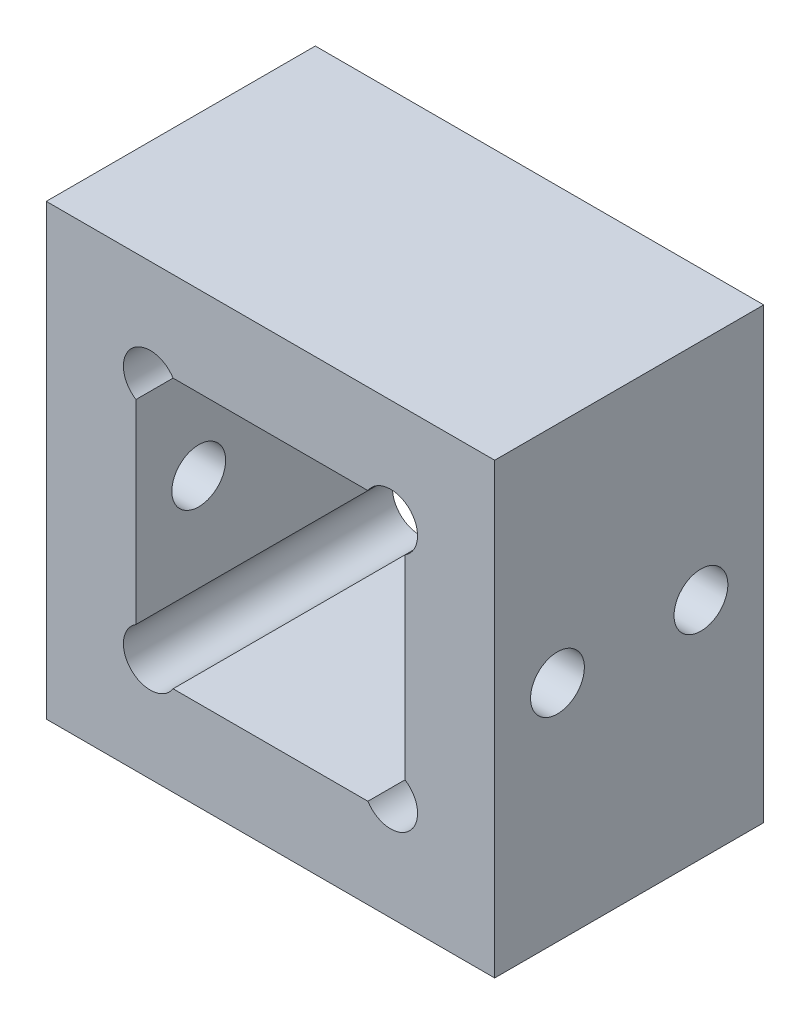
SolidWorks part; units mm, degrees
material "POM 乙缩醛共聚物"
ref_plane "前视基准面" through (0, 0, 0) normal (0, 0, 1) x (1, 0, 0)
ref_plane "上视基准面" through (0, 0, 0) normal (0, 1, 0) x (1, 0, 0)
ref_plane "右视基准面" through (0, 0, 0) normal (1, 0, 0) x (0, 0, -1)
sketch "草图1" plane through (0, 0, 0) normal (0, 0, 1) x (1, 0, 0)
  line L0 (-12.5, 12.5) -> (12.5, 12.5)
  line L5 (-7.5, 7.5) -> (7.5, 7.5)
  line L6 (-7.5, 7.5) -> (-7.5, -7.5)
  line L7 (-7.5, -7.5) -> (7.5, -7.5)
  line L21 (7.5, 7.5) -> (7.5, -7.5)
  line L22 (-7.5, 7.5) -> (7.5, -7.5) construction
  line L26 (-7.5, -7.5) -> (7.5, 7.5) construction
  line L31 (12.5, 12.5) -> (12.5, -12.5)
  line L32 (-12.5, -12.5) -> (12.5, -12.5)
  line L33 (-12.5, 12.5) -> (-12.5, -12.5)
  point P0 (0, 0)
  dimension "D1" = 15
  dimension "D2" = 15
  dimension "D3" = 25
  dimension "D4" = 25
extrude "凸台-拉伸1" add sketch "草图1" along normal blind 15
sketch "草图2" plane through (0, 0, 15) normal (0, 0, 1) x (1, 0, 0)
  line L4 (-7.5, 7.5) -> (7.5, -7.5) construction
  line L5 (7.5, 7.5) -> (-7.5, -7.5) construction
  line L6 (7.5, 7.5) -> (-7.5, 7.5) construction
  line L7 (-7.5, -7.5) -> (7.5, -7.5) construction
  circle A4 centre (6.7, 6.7) radius 1.5
  circle A5 centre (6.7, -6.7) radius 1.5
  circle A6 centre (-6.7, -6.7) radius 1.5
  circle A7 centre (-6.7, 6.7) radius 1.5
  point P12 (0, 0)
  point P13 (0, 0)
  point P14 (0, 0)
  point P15 (0, 0)
  point P16 (0, 0)
  dimension "D1" = 3
  dimension "D2" = 0.8
  dimension "D3" = 0.8
  dimension "D4" = 0.8
  dimension "D5" = 0.8
extrude "切除-拉伸1" cut sketch "草图2" against normal through all
sketch "草图3" plane through (12.5, 0, 0) normal (1, 0, 0) x (0, 0, -1)
  line L0 (-15, 0) -> (0, 0) construction
  line L1 (-15, -12.5) -> (-15, 12.5) construction
  line L2 (-7.5, 0) -> (-7.5, 12.5) construction
  line L3 (-15, 12.5) -> (0, 12.5) construction
  circle A0 centre (-11.5, 0) radius 1.5
  circle A1 centre (-3.5, 0) radius 1.5
  dimension "D1" = 4
  dimension "D2" = 3
extrude "切除-拉伸2" cut sketch "草图3" against normal through all
